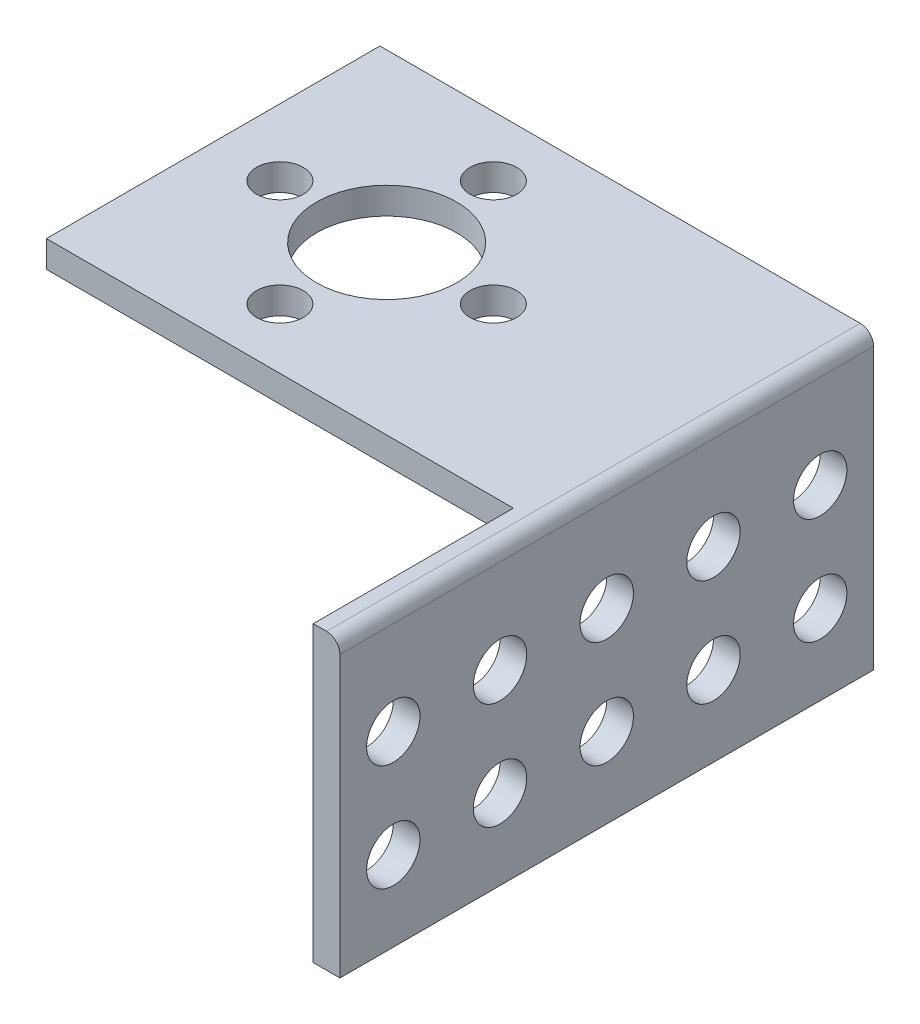
SolidWorks part; units mm, degrees
material "AISI 304"
ref_plane "前视基准面" through (0, 0, 0) normal (0, 0, 1) x (1, 0, 0)
ref_plane "上视基准面" through (0, 0, 0) normal (0, 1, 0) x (1, 0, 0)
ref_plane "右视基准面" through (0, 0, 0) normal (1, 0, 0) x (0, 0, -1)
sketch "Sketch1" plane through (0, 0, 0) normal (0, 1, 0) x (1, 0, 0)
  line L0 (0, 0) -> (0, -25)
  line L1 (0, -25) -> (35, -25)
  line L2 (35, -25) -> (35, 0)
  line L3 (35, 0) -> (0, 0)
  line L6 (13, 1.3433) -> (13, -25.9721) construction
  circle A0 centre (13, -12.5) radius 5.25
  circle A1 centre (13, -12.5) radius 8 construction
  circle A2 centre (13, -4.5) radius 1.75
  circle A3 centre (21, -12.5) radius 1.75
  circle A4 centre (13, -20.5) radius 1.75
  circle A5 centre (5, -12.5) radius 1.75
  point P21 (13, -12.5)
  dimension "D3" = 10.5
  dimension "D4" = 16
  dimension "D5" = 3.5
  dimension "D7" = 8
  dimension "D1" = 25
  dimension "D2" = 35
  dimension "D8" = 8
  dimension "D9" = 12.5
  dimension "D10" = 13
  dimension "D6" = 4
extrude "Boss-Extrude1" add sketch "Sketch1" along normal blind 2
sketch "Sketch2" plane through (35, 0, 0) normal (1, 0, 0) x (0, 0, -1)
  line L0 (-25, 2) -> (-40, 2)
  line L1 (-40, 2) -> (-40, -20)
  line L2 (-40, -20) -> (0, -20)
  line L3 (0, -20) -> (0, 2)
  line L4 (0, 2) -> (-25, 2)
  line L5 (-12.5, 7.7883) -> (-12.5, -22.0736) construction
  line L6 (-25, 2) -> (-25, 0) construction
  dimension "D1" = 40
  dimension "D2" = 22
  dimension "D3" = 12.5
  dimension "D4" = 27.5
extrude "Boss-Extrude2" add sketch "Sketch2" along normal blind 2
sketch "Sketch3" plane through (37, 0, 0) normal (1, 0, 0) x (0, 0, -1)
  line L0 (0, 2) -> (-40, 2) construction
  line L1 (0, -20) -> (0, 2) construction
  circle A0 centre (-20, -6) radius 2
  circle A1 centre (-12, -6) radius 2
  circle A2 centre (-4, -6) radius 2
  circle A3 centre (-28, -6) radius 2
  circle A4 centre (-36, -6) radius 2
  circle A5 centre (-36, -14) radius 2
  circle A6 centre (-28, -14) radius 2
  circle A7 centre (-20, -14) radius 2
  circle A8 centre (-12, -14) radius 2
  circle A9 centre (-4, -14) radius 2
  dimension "D1" = 4
  dimension "D4" = 16
  dimension "D5" = 16
  dimension "D6" = 8
  dimension "D7" = 20
  dimension "D2" = 3
  dimension "D3" = 3
  dimension "D8" = 2
extrude "Cut-Extrude1" cut sketch "Sketch3" against normal through all
fillet "Fillet1" radius 1 1 edges at (37, 2, 20)
fillet "Fillet2" radius 0.5 1 edges at (35, 0, 12.5)
